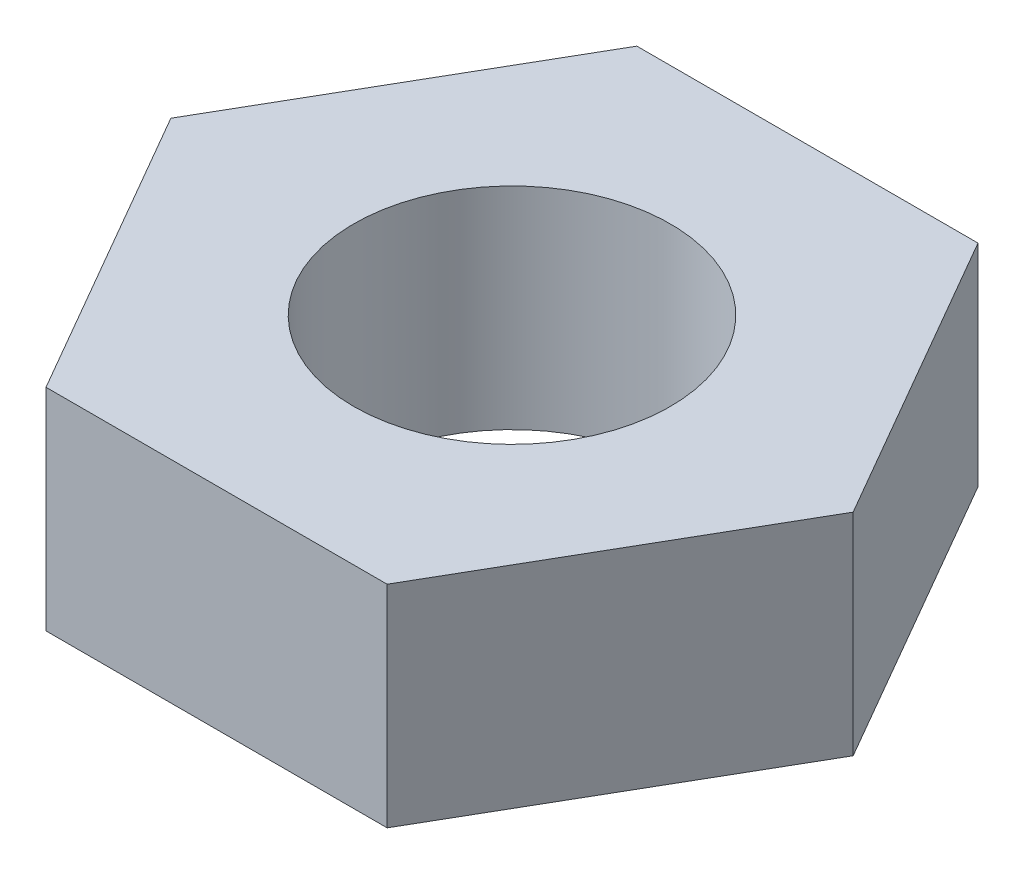
SolidWorks part; units mm, degrees
ref_plane "Front Plane" through (0, 0, 0) normal (0, 0, 1) x (1, 0, 0)
ref_plane "Top Plane" through (0, 0, 0) normal (0, 1, 0) x (1, 0, 0)
ref_plane "Right Plane" through (0, 0, 0) normal (1, 0, 0) x (0, 0, -1)
sketch "Sketch1" plane through (0, 0, 0) normal (0, 1, 0) x (1, 0, 0)
  line L1 (2.0531, 3.556) -> (-2.0531, 3.556)
  line L2 (-2.0531, 3.556) -> (-4.1061, 0)
  line L3 (-4.1061, 0) -> (-2.0531, -3.556)
  line L4 (-2.0531, -3.556) -> (2.0531, -3.556)
  line L5 (2.0531, -3.556) -> (4.1061, 0)
  line L6 (4.1061, 0) -> (2.0531, 3.556)
  circle A0 centre (0, 0) radius 3.556 construction
  circle A1 centre (0, 0) radius 1.905
  dimension "D1" = 7.112
  dimension "D2" = 3.81
extrude "Boss-Extrude1" add sketch "Sketch1" against normal blind 2.54
